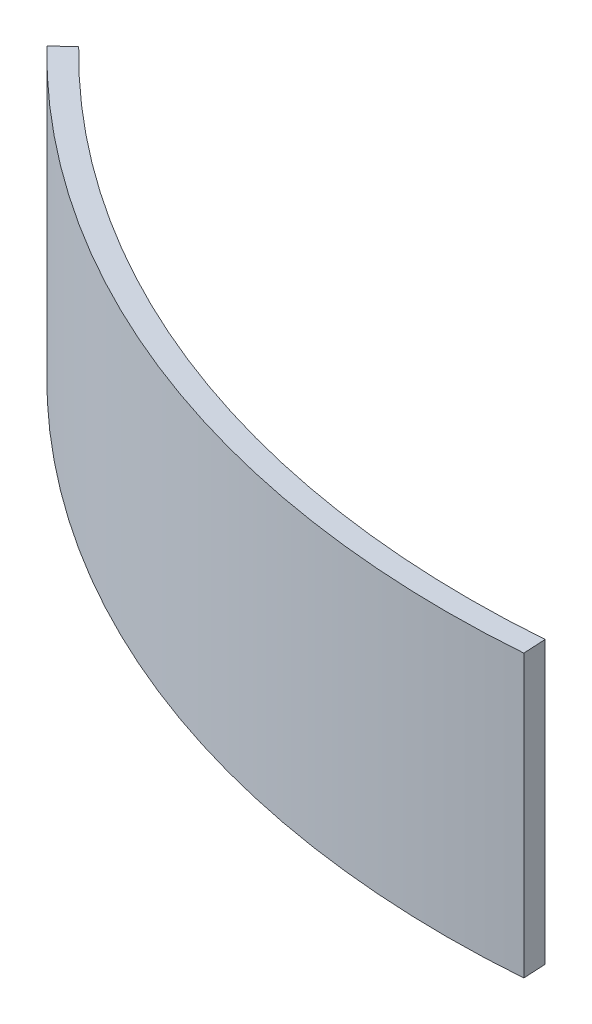
SolidWorks part; units mm, degrees
ref_plane "Front Plane" through (0, 0, 0) normal (0, 0, 1) x (1, 0, 0)
ref_plane "Top Plane" through (0, 0, 0) normal (0, 1, 0) x (1, 0, 0)
ref_plane "Right Plane" through (0, 0, 0) normal (1, 0, 0) x (0, 0, -1)
sketch "Sketch1" plane through (0, 0, 0) normal (1, 0, 0) x (0, 0, -1)
  line L1 (0, 0) -> (2, 0)
  line L2 (0, 0) -> (0, -25)
  line L3 (0, -25) -> (2, -25)
  line L4 (2, 0) -> (2, -25)
  dimension "D1" = 25
  dimension "D2" = 2
sketch "Sketch2" plane through (0, 0, 0) normal (0, 1, 0) x (1, 0, 0)
  line L0 (0, 0) -> (0, 2) construction
  line L1 (-1.9616, 85.8023) -> (-62.5523, 26.4387) construction
  line L2 (-1.9616, 85.8023) -> (4.5666, 1.2289) construction
  arc A0 (-62.5523, 26.4387) -> (4.5666, 1.2289) centre (-1.9616, 85.8023) ccw
  point P4 (0, 1)
  dimension "D1" = 169.65
  dimension "D2" = 50
sweep "Sweep1" add profiles "Sketch1" path "Sketch2"
equation "\"D1@Sketch2\"=339.30mm/2"
